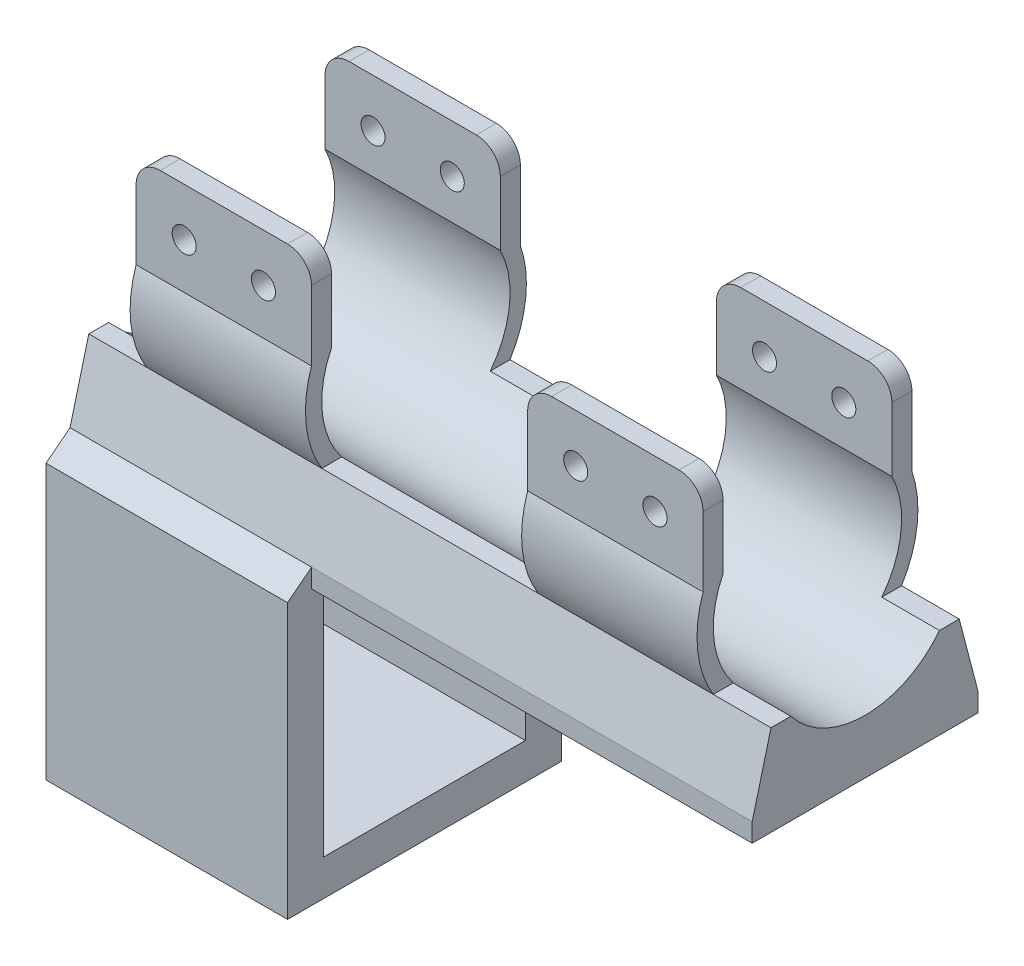
SolidWorks part; units mm, degrees
ref_plane "前视基准面" through (0, 0, 0) normal (0, 0, 1) x (1, 0, 0)
ref_plane "上视基准面" through (0, 0, 0) normal (0, 1, 0) x (1, 0, 0)
ref_plane "右视基准面" through (0, 0, 0) normal (1, 0, 0) x (0, 0, -1)
sketch "Sketch1" plane through (0, 0, 0) normal (0, 1, 0) x (1, 0, 0)
  line L1 (-1010.6648, 38.8562) -> (-868.6648, 38.8562)
  line L2 (-1010.6648, 38.8562) -> (-1010.6648, -8.1438)
  line L3 (-1010.6648, -8.1438) -> (-868.6648, -8.1438)
  line L4 (-868.6648, 38.8562) -> (-868.6648, -8.1438)
  dimension "D1" = 142
  dimension "D2" = 47
extrude "Boss-Extrude1" add sketch "Sketch1" along normal blind 110
sketch "Sketch2" plane through (-868.6648, 0, 0) normal (1, 0, 0) x (0, 0, -1)
  line L0 (-8.1438, 110) -> (-8.1438, 0) construction
  line L1 (-5.6438, 52.1) -> (36.3562, 52.1)
  line L2 (-5.6438, 52.1) -> (-5.6438, 2.5)
  line L3 (-5.6438, 2.5) -> (36.3562, 2.5)
  line L4 (36.3562, 52.1) -> (36.3562, 2.5)
  line L6 (-8.1438, 0) -> (38.8562, 0) construction
  dimension "D1" = 49.6
  dimension "D2" = 42
  dimension "D3" = 2.5
  dimension "D4" = 2.5
extrude "Cut-Extrude1" cut sketch "Sketch2" against normal blind 137
sketch "Sketch4" plane through (0, 0, 0) normal (0, -1, 0) x (1, 0, 0)
  line L0 (-1010.6648, 8.1438) -> (-868.6648, 8.1438) construction
  line L1 (-960.3868, 8.1438) -> (-926.7882, 8.1438)
  line L2 (-960.3868, 8.1438) -> (-960.3868, -38.8562)
  line L3 (-960.3868, -38.8562) -> (-926.7882, -38.8562)
  line L4 (-926.7882, 8.1438) -> (-926.7882, -38.8562)
  line L5 (-868.6648, -38.8562) -> (-1010.6648, -38.8562) construction
extrude "Cut-Extrude3" cut sketch "Sketch4" against normal blind 10
sketch "Sketch5" plane through (-868.6648, 0, 0) normal (1, 0, 0) x (0, 0, -1)
  line L0 (-8.1438, 56) -> (38.8562, 56) construction
  line L1 (-8.1438, 110) -> (-8.1438, 0) construction
  line L2 (38.8562, 110) -> (38.8562, 0) construction
  line L3 (-8.1438, 110) -> (38.8562, 110) construction
  line L4 (-8.1438, 110) -> (38.8562, 56) construction
  line L5 (38.8562, 110) -> (-8.1438, 56) construction
  line L6 (-2.2131, 110) -> (-2.2131, 91.6879)
  line L7 (-8.1438, 56) -> (-4.2395, 70.9677)
  line L8 (15.3562, 83) -> (15.3562, 133.961) construction
  line L9 (38.8562, 56) -> (34.9519, 70.9677)
  line L10 (-2.2131, 110) -> (-8.1438, 110)
  line L11 (-12.866, 110) -> (-8.1438, 110)
  line L12 (-8.1438, 110) -> (-8.1438, 56)
  line L13 (-8.1438, 56) -> (-14.713, 56)
  line L14 (19.5784, 110) -> (38.8562, 110)
  line L15 (38.8562, 110) -> (38.8562, 56)
  line L16 (38.8562, 56) -> (21.2492, 56)
  line L17 (-8.1438, 56) -> (38.8562, 56)
  line L18 (38.8562, 110) -> (32.9255, 110)
  line L19 (32.9255, 110) -> (32.9255, 91.6879)
  line L20 (-6.3809, 110) -> (-6.3809, 90.5011)
  line L21 (-1.9692, 110) -> (-8.1438, 110)
  line L22 (-8.1438, 56) -> (-14.713, 56)
  line L23 (32.6816, 110) -> (38.8562, 110)
  line L24 (38.8562, 56) -> (45.4254, 56)
  line L25 (-2.2131, 110) -> (32.9255, 110)
  line L26 (-2.2131, 91.6879) -> (-2.2131, 97.8354)
  line L27 (32.9255, 91.6879) -> (32.9255, 97.8354)
  line L28 (37.0981, 110) -> (37.0981, 90.4872)
  arc A2 (-2.2131, 91.6879) -> (32.9255, 91.6879) centre (15.3562, 83) ccw
  arc A4 (-2.2131, 97.8354) -> (32.9255, 97.8354) centre (15.3562, 83) ccw
  dimension "D2" = 19.6
  dimension "D1" = 54
extrude "Cut-Extrude9" cut sketch "Sketch5" against normal through all
sketch "Sketch8" plane through (0, 0, 8.1438) normal (0, 0, 1) x (1, 0, 0)
  line L0 (-1010.6648, 70.9677) -> (-868.6648, 70.9677) construction
  line L1 (-1010.6648, 110) -> (-998.6648, 110)
  line L2 (-1010.6648, 110) -> (-1010.6648, 70.9677)
  line L3 (-1010.6648, 70.9677) -> (-998.6648, 70.9677)
  line L4 (-998.6648, 110) -> (-998.6648, 70.9677)
  line L6 (-868.6648, 110) -> (-880.6648, 110)
  line L7 (-868.6648, 110) -> (-868.6648, 70.9677)
  line L8 (-868.6648, 70.9677) -> (-880.6648, 70.9677)
  line L9 (-880.6648, 110) -> (-880.6648, 70.9677)
  line L10 (-962.1648, 110) -> (-917.1648, 110)
  line L11 (-962.1648, 110) -> (-962.1648, 70.9677)
  line L12 (-962.1648, 70.9677) -> (-917.1648, 70.9677)
  line L13 (-917.1648, 110) -> (-917.1648, 70.9677)
  line L14 (-998.6648, 110) -> (-962.1648, 110)
  line L15 (-917.1648, 110) -> (-880.6648, 110)
  dimension "D1" = 12
  dimension "D2" = 12
  dimension "D3" = 45
extrude "Cut-Extrude12" cut sketch "Sketch8" against normal through all contours L4 L1 L2 L3 | L13 L10 L11 L12 | L6 L9 L8 L7
sketch "Sketch11" plane through (0, 0, 6.3809) normal (0, 0, 1) x (1, 0, 0)
  line L0 (-998.6648, 110) -> (-962.1648, 110) construction
  line L1 (-998.6648, 110) -> (-998.6648, 90.5011) construction
  line L2 (-962.1648, 110) -> (-962.1648, 90.5011) construction
  line L4 (-917.1648, 110) -> (-880.6648, 110) construction
  line L5 (-917.1648, 110) -> (-917.1648, 90.5011) construction
  line L6 (-880.6648, 110) -> (-880.6648, 90.5011) construction
  circle A0 centre (-988.6648, 100) radius 2.5
  circle A1 centre (-972.1648, 100) radius 2.5
  circle A2 centre (-907.1648, 100) radius 2.5
  circle A3 centre (-890.6648, 100) radius 2.5
  dimension "D5" = 5
  dimension "D6" = 5
  dimension "D11" = 5
  dimension "D12" = 5
  dimension "D1" = 10
  dimension "D2" = 10
  dimension "D3" = 10
  dimension "D4" = 10
  dimension "D7" = 10
  dimension "D8" = 10
  dimension "D9" = 10
  dimension "D10" = 10
extrude "Cut-Extrude13" cut sketch "Sketch11" against normal through all
fillet "Fillet5" radius 5 8 edges at (-998.6648, 110, -35.0118) (-917.1648, 110, -35.0118) (-962.1648, 110, -35.0118) (-880.6648, 110, -35.0118) (-880.6648, 110, 4.297) (-917.1648, 110, 4.297) (-962.1648, 110, 4.297) (-998.6648, 110, 4.297)
sketch "Sketch13" plane through (-868.6648, 0, 0) normal (1, 0, 0) x (0, 0, -1)
  line L0 (38.8562, 56) -> (38.8562, 0) construction
  line L1 (-8.1438, 0) -> (38.8562, 0)
  line L2 (-8.1438, 0) -> (-8.1438, 52.1)
  line L3 (-8.1438, 52.1) -> (38.8562, 52.1)
  line L4 (38.8562, 0) -> (38.8562, 52.1)
  line L5 (36.3562, 52.1) -> (-5.6438, 52.1) construction
extrude "Cut-Extrude14" cut sketch "Sketch13" against normal up to surface (91.722 mm away) up to face at (-960.3868, 5.625, -15.3562)
sketch "Sketch15" plane through (-960.3868, 0, 0) normal (1, 0, 0) x (0, 0, -1)
  line L0 (-8.1438, 52.1) -> (-13.1438, 52.1)
  line L1 (-13.1438, 52.1) -> (-13.1438, -5)
  line L2 (-13.1438, -5) -> (43.8562, -5)
  line L3 (43.8562, -5) -> (43.8562, 52.1)
  line L4 (43.8562, 52.1) -> (38.8562, 52.1)
  line L5 (-8.1438, 0) -> (38.8562, 0) construction
  line L6 (-8.1438, 52.1) -> (-8.1438, 0)
  line L7 (-8.1438, 0) -> (38.8562, 0)
  line L8 (38.8562, 0) -> (38.8562, 52.1)
  dimension "D1" = 5
  dimension "D2" = 5
  dimension "D3" = 5
extrude "Boss-Extrude2" add sketch "Sketch15" against normal up to surface (50.278 mm away) up to face at (-1010.6648, 48.5379, -15.3562)
sketch "Sketch16" plane through (-1010.6648, 0, 0) normal (-1, 0, 0) x (0, 0, 1)
  line L0 (-38.8562, 56) -> (-43.8562, 52.1)
  line L1 (8.1438, 56) -> (13.1438, 52.1)
  line L2 (13.1438, 52.1) -> (8.1438, 52.1)
  line L3 (8.1438, 52.1) -> (8.1438, 56)
  line L4 (-38.8562, 56) -> (-38.8562, 52.1)
  line L5 (-38.8562, 52.1) -> (-43.8562, 52.1)
extrude "Boss-Extrude3" add sketch "Sketch16" against normal up to surface (50.278 mm away) up to face at (-960.3868, 30.76, -15.3562)
sketch "Sketch17" plane through (-1005.6648, 0, 0) normal (1, 0, 0) x (0, 0, -1)
  line L1 (-5.6438, 52.1) -> (36.3562, 52.1)
  line L2 (-5.6438, 52.1) -> (-5.6438, 2.5)
  line L3 (-5.6438, 2.5) -> (36.3562, 2.5)
  line L4 (36.3562, 52.1) -> (36.3562, 2.5)
extrude "Cut-Extrude15" cut sketch "Sketch17" against normal through all
sketch "Sketch18" plane through (-1010.6648, 0, 0) normal (-1, 0, 0) x (0, 0, 1)
  line L0 (13.1438, 52.1) -> (13.1438, -5) construction
  line L1 (-43.8562, 1) -> (-40.1062, 1) construction
  line L2 (-43.8562, 52.1) -> (-43.8562, -5) construction
  line L3 (-40.1062, 1) -> (-36.3562, 1) construction
  line L4 (-36.3562, 2.5) -> (-36.3562, 52.1) construction
  line L5 (-40.1062, 1) -> (-40.1062, -5) construction
  line L6 (-43.8562, -5) -> (13.1438, -5) construction
  line L7 (5.6438, 1) -> (9.3938, 1) construction
  line L8 (5.6438, 52.1) -> (5.6438, 2.5) construction
  line L9 (9.3938, 1) -> (13.1438, 1) construction
  line L10 (13.1438, -5) -> (13.1438, 52.1) construction
  line L11 (13.1438, 1) -> (13.1438, -5) construction
  line L12 (-36.3562, 52.1) -> (5.6438, 52.1) construction
  line L13 (-36.3562, 52.1) -> (-36.3562, 2.5) construction
  line L14 (-36.3562, 52.1) -> (5.6438, 52.1) construction
  line L15 (-43.8562, -5) -> (13.1438, -5) construction
  circle A0 centre (-40.1062, 1) radius 3
  circle A1 centre (9.3938, 1) radius 3
  circle A2 centre (-40.1062, 46) radius 3
  circle A3 centre (9.3938, 46) radius 3
  dimension "D1" = 45
  dimension "D2" = 6.1
hole_wizard "M6 Tapped Hole1" positions "3DSketch1" profile "Sketch20" tap size "M6" standard "GB"
sketch3d "3DSketch1"
  point P0 (-1010.6648, 46, -40.1062)
  point P3 (-1010.6648, 1, -40.1062)
  point P6 (-1010.6648, 1, 9.3938)
  point P9 (-1010.6648, 46, 9.3938)
sketch "Sketch20" plane through (-1010.6648, 46, -40.1062) normal (0, 1, 0) x (0, 0, 1)
  line L0 (0, 0) -> (0, 16.5022)
  line L1 (0, 16.5022) -> (2.5, 15)
  line L2 (2.5, 15) -> (2.5, 0)
  line L5 (2.5, 0) -> (0, 0)
  line L10 (0, 16.5022) -> (-2.5, 15) construction
  line L11 (0, -6.35) -> (0, 107.95) construction
  dimension "Tap Drill Dia." = 5
  dimension "Tap Drill Depth" = 15
  dimension "Drill Angle" = 118
cosmetic thread "Hole Thread1" parameters "D1"=12, "D2"=6
cosmetic thread "Hole Thread2" parameters "D1"=12, "D2"=6
cosmetic thread "Hole Thread3" parameters "D1"=12, "D2"=6
cosmetic thread "Hole Thread4" parameters "D1"=12, "D2"=6
